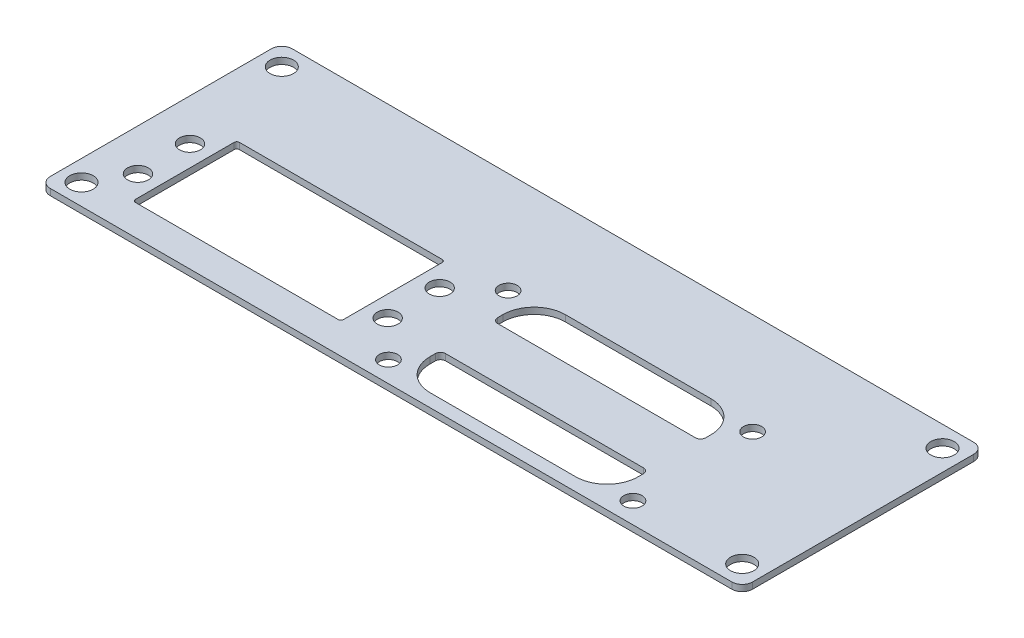
SolidWorks part; units mm, degrees
material "1023 Carbon Steel Sheet (SS)"
ref_plane "Front Plane" through (0, 0, 0) normal (0, 0, 1) x (1, 0, 0)
ref_plane "Top Plane" through (0, 0, 0) normal (0, 1, 0) x (1, 0, 0)
ref_plane "Right Plane" through (0, 0, 0) normal (1, 0, 0) x (0, 0, -1)
sketch "BASE" plane through (0, 0, 0) normal (0, 1, 0) x (1, 0, 0)
  line L0 (63.5, 19.25) -> (-63.5, 19.25) construction
  line L1 (65.5, -23.25) -> (-65.5, -23.25)
  line L2 (67.5, -21.25) -> (67.5, 21.25)
  line L3 (65.5, 23.25) -> (-65.5, 23.25)
  line L4 (-67.5, -21.25) -> (-67.5, 21.25)
  line L5 (67.5, -23.25) -> (-67.5, 23.25) construction
  line L6 (67.5, 23.25) -> (-67.5, -23.25) construction
  line L11 (-4.5, 3.75) -> (42.5, -19.25) construction
  line L12 (-4.5, -19.25) -> (42.5, 3.75) construction
  line L13 (-67.5, 0) -> (67.5, 0) construction
  line L14 (-63.5, -19.25) -> (-63.5, 19.25) construction
  line L15 (63.5, -19.25) -> (-63.5, -19.25) construction
  line L16 (63.5, -19.25) -> (63.5, 19.25) construction
  line L17 (-4.5, -19.25) -> (-4.5, 3.75) construction
  line L18 (-4.5, 3.75) -> (42.5, 3.75) construction
  line L19 (42.5, -19.25) -> (42.5, 3.75) construction
  line L20 (-4.5, -19.25) -> (42.5, -19.25) construction
  line L21 (67.5, -23.25) -> (67.5, 23.25) construction
  line L22 (67.5, -23.25) -> (-67.5, -23.25) construction
  line L23 (67.5, 23.25) -> (-67.5, 23.25) construction
  line L24 (-67.5, -23.25) -> (-67.5, 23.25) construction
  line L25 (-59.5, 0) -> (-24.5, 0) construction
  line L27 (42.5, 3.75) -> (42.5, -19.25) construction
  line L28 (-59.5, -12.4) -> (-11.5, -12.4) construction
  line L29 (34.42, -20.42) -> (57.5, -20.42) construction
  line L30 (34.42, -20.42) -> (34.42, 20.42) construction
  line L31 (34.42, 20.42) -> (57.5, 20.42) construction
  line L32 (5, -20.75) -> (33, -20.75)
  line L33 (-1, -14.75) -> (-1, -13.75)
  line L34 (5, 5.25) -> (33, 5.25)
  line L35 (39, -14.75) -> (39, -13.75)
  line L36 (-1, -20.75) -> (39, 5.25) construction
  line L37 (-1, 5.25) -> (39, -20.75) construction
  line L38 (57.5, -20.42) -> (57.5, 20.42) construction
  line L39 (34.42, -20.42) -> (57.5, 20.42) construction
  line L40 (34.42, 20.42) -> (57.5, -20.42) construction
  line L41 (-59.5, -12.4) -> (-59.5, -2.4) construction
  line L42 (-59.5, -2.4) -> (-11.5, -2.4) construction
  line L43 (-11.5, -12.4) -> (-11.5, -2.4) construction
  line L44 (-59.5, -12.4) -> (-11.5, -2.4) construction
  line L45 (-59.5, -2.4) -> (-11.5, -12.4) construction
  line L46 (-55, -17.4) -> (-16, -17.4)
  line L47 (-55.5, -16.9) -> (-55.5, 2.1)
  line L48 (-55, 2.6) -> (-16, 2.6)
  line L49 (-15.5, -16.9) -> (-15.5, 2.1)
  line L50 (-55.5, -17.4) -> (-15.5, 2.6) construction
  line L51 (-55.5, 2.6) -> (-15.5, -17.4) construction
  line L52 (-1, -1.75) -> (-1, -0.75)
  line L53 (0, -12.75) -> (38, -12.75)
  line L55 (0, -2.75) -> (38, -2.75)
  line L57 (-1, -12.75) -> (39, -2.75) construction
  line L58 (-1, -2.75) -> (39, -12.75) construction
  line L59 (39, -1.75) -> (39, -0.75)
  circle A6 centre (-63.5, 19.25) radius 2.25
  circle A7 centre (-63.5, -19.25) radius 2.25
  circle A8 centre (63.5, -19.25) radius 2.25
  circle A9 centre (63.5, 19.25) radius 2.25
  circle A12 centre (-4.5, 3.75) radius 1.75
  circle A13 centre (42.5, 3.75) radius 1.75
  circle A14 centre (42.5, -19.25) radius 1.75
  circle A15 centre (-4.5, -19.25) radius 1.75
  arc A16 (67.5, -21.25) -> (65.5, -23.25) centre (65.5, -21.25) cw
  arc A17 (65.5, 23.25) -> (67.5, 21.25) centre (65.5, 21.25) cw
  arc A18 (-65.5, 23.25) -> (-67.5, 21.25) centre (-65.5, 21.25) ccw
  arc A19 (-65.5, -23.25) -> (-67.5, -21.25) centre (-65.5, -21.25) cw
  arc A29 (-1, -0.75) -> (5, 5.25) centre (5, -0.75) cw
  arc A30 (5, -20.75) -> (-1, -14.75) centre (5, -14.75) cw
  arc A31 (33, -20.75) -> (39, -14.75) centre (33, -14.75) ccw
  arc A32 (39, -0.75) -> (33, 5.25) centre (33, -0.75) ccw
  arc A33 (-55.5, -16.9) -> (-55, -17.4) centre (-55, -16.9) ccw
  arc A34 (-16, -17.4) -> (-15.5, -16.9) centre (-16, -16.9) ccw
  arc A35 (-15.5, 2.1) -> (-16, 2.6) centre (-16, 2.1) ccw
  arc A36 (-55, 2.6) -> (-55.5, 2.1) centre (-55, 2.1) ccw
  circle A37 centre (-45.5, -7.4) radius 12.05 construction
  circle A38 centre (-59.5, -2.4) radius 2
  circle A39 centre (-59.5, -12.4) radius 2
  circle A40 centre (-11.5, -2.4) radius 2
  circle A41 centre (-11.5, -12.4) radius 2
  arc A42 (38, -2.75) -> (39, -1.75) centre (38, -1.75) ccw
  arc A43 (38, -12.75) -> (39, -13.75) centre (38, -13.75) cw
  arc A44 (0, -12.75) -> (-1, -13.75) centre (0, -13.75) ccw
  arc A45 (-1, -1.75) -> (0, -2.75) centre (0, -1.75) ccw
  point P0 (0, 0)
  point P6 (45.96, 0)
  point P16 (-35.5, -7.4)
  point P51 (-35.5, -7.4)
  point P67 (19, -7.75)
  point P85 (-45.5, -7.4)
  point P89 (19, -7.75)
  point P92 (-45.5, 4.65)
  point P93 (19, -7.75)
  dimension "D6" = 4.5
  dimension "D7" = 4
  dimension "D8" = 23.08
  dimension "D9" = 40.84
  dimension "D15" = 3.5
  dimension "D16" = 2
  dimension "D17" = 20
  dimension "D19" = 0.5
  dimension "D20" = 10
  dimension "D22" = 4
  dimension "D23" = 4
  dimension "D25" = 6
  dimension "D26" = 47
  dimension "D11" = 10
  dimension "D21" = 24.1
  dimension "D30" = 1
  dimension "D1" = 46.5
  dimension "D2" = 135
  dimension "D3" = 26
  dimension "D4" = 48
  dimension "D5" = 35
  dimension "D10" = 10
  dimension "D12" = 8
  dimension "D14" = 25
  dimension "D18" = 40
  dimension "D13" = 23
  dimension "D24" = 40
  dimension "D27" = 2.4
  dimension "D28" = 4.65
  dimension "D29" = 10
extrude "SHEET" add sketch "BASE" along normal blind 1.2192
